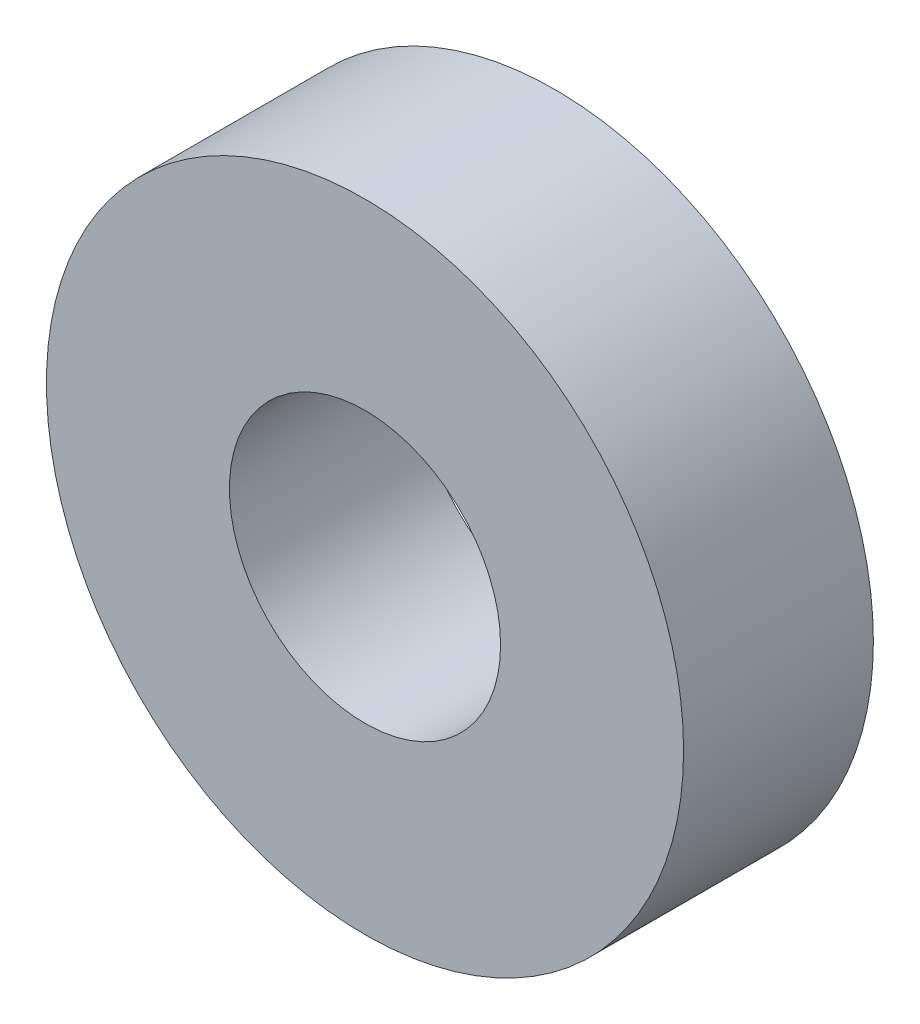
SolidWorks part; units mm, degrees
ref_plane "Спереди" through (0, 0, 0) normal (0, 0, 1) x (1, 0, 0)
ref_plane "Сверху" through (0, 0, 0) normal (0, 1, 0) x (1, 0, 0)
ref_plane "Справа" through (0, 0, 0) normal (1, 0, 0) x (0, 0, -1)
sketch "Эскиз1" plane through (0, 0, 0) normal (0, 0, 1) x (1, 0, 0)
  circle A0 centre (0, 0) radius 23.5
  circle A1 centre (0, 0) radius 10
extrude "Purchased_bearing_envelope" add sketch "Эскиз1" along normal blind 14 from offset 26
